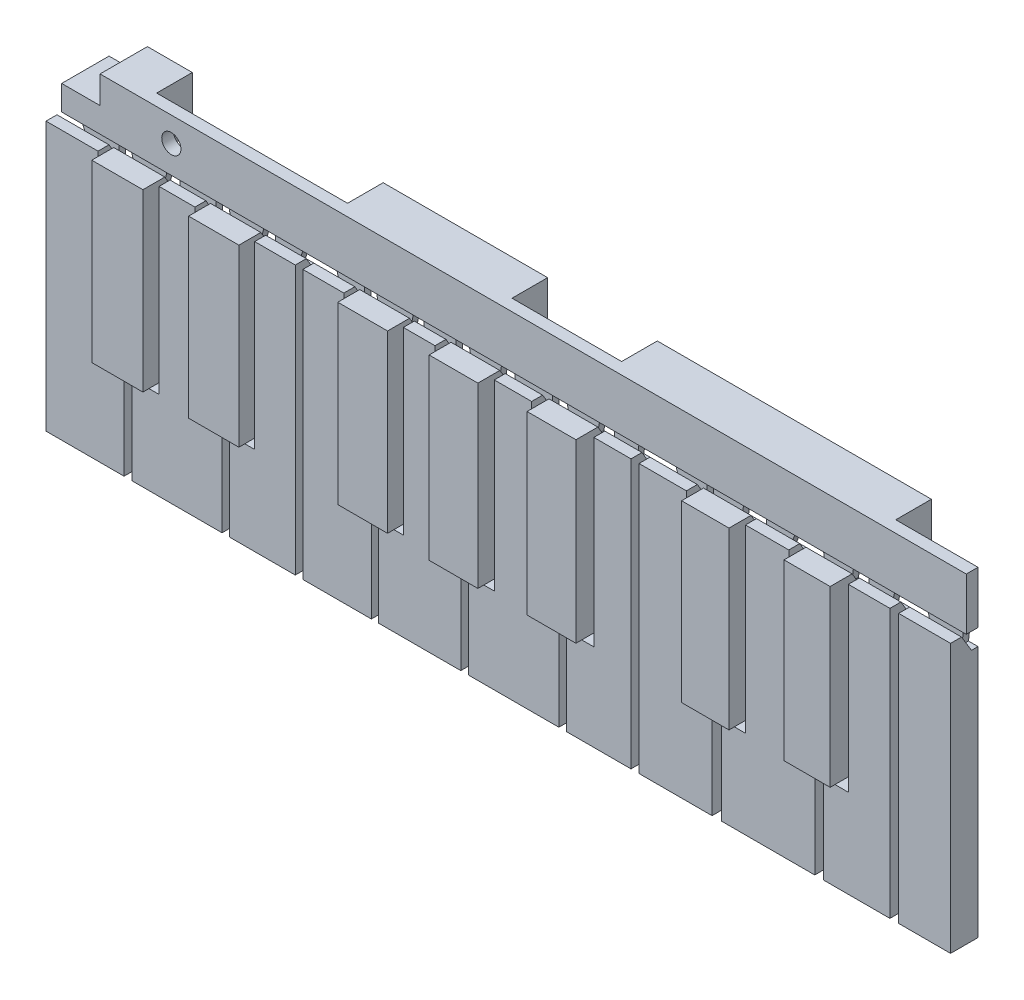
SolidWorks part; units mm, degrees
ref_plane "前视基准面" through (0, 0, 0) normal (0, 0, 1) x (1, 0, 0)
ref_plane "上视基准面" through (0, 0, 0) normal (0, 1, 0) x (1, 0, 0)
ref_plane "右视基准面" through (0, 0, 0) normal (1, 0, 0) x (0, 0, -1)
sketch "草图1" plane through (0, 0, 0) normal (0, 0, 1) x (1, 0, 0)
  line L1 (-72.6119, 33.3575) -> (92.3881, 33.3575)
  line L2 (-72.6119, 33.3575) -> (-72.6119, -26.6425)
  line L3 (-72.6119, -26.6425) -> (92.3881, -26.6425)
  line L4 (92.3881, 33.3575) -> (92.3881, -26.6425)
  dimension "D1" = 165
  dimension "D2" = 60
extrude "凸台-拉伸1" add sketch "草图1" along normal blind 5
sketch "草图2" plane through (0, 0, 5) normal (0, 0, 1) x (1, 0, 0)
  line L0 (-72.6119, 33.3575) -> (-72.6119, -26.6425) construction
  line L1 (92.3881, 33.3575) -> (-72.6119, 33.3575) construction
  circle A0 centre (-52.6119, 27.3575) radius 1.75
  dimension "D1" = 3.5
  dimension "D2" = 20
  dimension "D3" = 6
extrude "切除-拉伸1" cut sketch "草图2" against normal blind 30
sketch "草图3" plane through (0, 0, 5) normal (0, 0, 1) x (1, 0, 0)
  line L0 (-57.6119, 33.3575) -> (-57.6119, 22.3365)
  line L1 (92.3881, 33.3575) -> (-72.6119, 33.3575) construction
  line L2 (-72.6119, -26.6425) -> (92.3881, -26.6425) construction
  line L3 (-72.6119, 33.3575) -> (-72.6119, -26.6425) construction
  line L4 (-42.6119, 22.3365) -> (-42.6119, 33.3575)
  line L5 (-27.6119, 22.3365) -> (-27.6119, 33.3575)
  line L6 (-12.6119, 22.3365) -> (-12.6119, 33.3575)
  line L7 (2.3881, 22.3365) -> (2.3881, 33.3575)
  line L8 (17.3881, 22.3365) -> (17.3881, 33.3575)
  line L9 (32.3881, 22.3365) -> (32.3881, 33.3575)
  line L10 (47.3881, 22.3365) -> (47.3881, 33.3575)
  line L11 (62.3881, 22.3365) -> (62.3881, 33.3575)
  line L12 (77.3881, 22.3365) -> (77.3881, 33.3575)
  line L13 (92.3881, -26.6425) -> (92.3881, 33.3575)
  line L14 (-63.1231, 22.3365) -> (-63.1231, -10.5291)
  line L15 (-72.6119, 33.3575) -> (92.3881, 33.3575)
  line L16 (-72.6119, 33.3575) -> (-72.6119, 22.3365)
  line L17 (-72.6119, 22.3365) -> (92.3881, 22.3365)
  line L18 (92.3881, 33.3575) -> (92.3881, 22.3365)
  line L19 (-62.2658, 22.3365) -> (-52.9387, 22.3365)
  line L20 (-62.2658, 22.3365) -> (-62.2658, -9.6307)
  line L21 (-62.2658, -9.6307) -> (-52.9387, -9.6307)
  line L22 (-52.9387, 22.3365) -> (-52.9387, -9.6307)
  line L23 (-44.5975, 22.3365) -> (-35.4264, 22.3365)
  line L24 (-44.5975, 22.3365) -> (-44.5975, -9.5883)
  line L25 (-44.5975, -9.5883) -> (-35.4264, -9.5883)
  line L26 (-35.4264, 22.3365) -> (-35.4264, -9.5883)
  line L27 (-17.3914, 22.3365) -> (-8.3121, 22.3365)
  line L28 (-17.3914, 22.3365) -> (-17.3914, -9.6307)
  line L29 (-17.3914, -9.6307) -> (-8.3121, -9.6307)
  line L30 (-8.3121, 22.3365) -> (-8.3121, -9.6307)
  line L31 (-0.7328, 22.3365) -> (8.1631, 22.3365)
  line L32 (-0.7328, 22.3365) -> (-0.7328, -10.1031)
  line L33 (-0.7328, -10.1031) -> (8.1631, -10.1031)
  line L34 (8.1631, 22.3365) -> (8.1631, -10.1031)
  line L35 (17.1354, 22.3365) -> (26.0513, 22.3365)
  line L36 (17.1354, 22.3365) -> (17.1354, -9.8183)
  line L37 (17.1354, -9.8183) -> (26.0513, -9.8183)
  line L38 (26.0513, 22.3365) -> (26.0513, -9.8183)
  line L39 (64.0101, 22.3365) -> (72.4216, 22.3365)
  line L40 (64.0101, 22.3365) -> (64.0101, -9.3895)
  line L41 (64.0101, -9.3895) -> (72.4216, -9.3895)
  line L42 (72.4216, 22.3365) -> (72.4216, -9.3895)
  line L43 (53.9662, 22.3365) -> (45.3232, 22.3365)
  line L44 (53.9662, 22.3365) -> (53.9662, -9.5503)
  line L45 (53.9662, -9.5503) -> (45.3232, -9.5503)
  line L46 (45.3232, 22.3365) -> (45.3232, -9.5503)
  line L47 (-63.1231, -10.5291) -> (-58.3767, -10.5291)
  line L48 (-58.3767, -10.5291) -> (-58.3767, -26.6425)
  line L49 (-51.9859, 22.3365) -> (-51.9859, -10.5291)
  line L50 (-51.9859, -10.5291) -> (-56.9239, -10.5291)
  line L51 (-56.9239, -10.5291) -> (-56.9239, -26.6425)
  line L52 (-45.4469, 22.3365) -> (-45.4469, -10.5043)
  line L53 (-45.4469, -10.5043) -> (-40.4974, -10.5043)
  line L54 (-40.4974, -10.5043) -> (-40.4974, -26.6425)
  line L55 (-34.5468, 22.3365) -> (-34.5468, -10.5043)
  line L56 (-34.5468, -10.5043) -> (-39.1403, -10.5043)
  line L57 (-39.1403, -10.5043) -> (-39.1403, -26.6425)
  line L58 (-27.14, 22.3365) -> (-27.14, -26.6425)
  line L59 (-25.7583, 22.3365) -> (-25.7583, -26.6425)
  line L60 (-18.2877, 22.3365) -> (-18.2877, -10.4718)
  line L61 (-18.2877, -10.4718) -> (-13.2634, -10.4718)
  line L62 (-13.2634, -10.4718) -> (-13.2634, -26.6425)
  line L63 (-7.4304, 22.3365) -> (-7.4304, -10.4718)
  line L64 (-7.4304, -10.4718) -> (-11.9858, -10.4718)
  line L65 (-11.9858, -10.4718) -> (-11.9858, -26.6425)
  line L66 (-1.6558, 22.3365) -> (-1.6558, -11.0171)
  line L67 (-1.6558, -11.0171) -> (3.0505, -11.0171)
  line L68 (3.0505, -11.0171) -> (3.0505, -26.6425)
  line L69 (9.158, 22.3365) -> (9.158, -11.0171)
  line L70 (9.158, -11.0171) -> (4.4188, -11.0171)
  line L71 (4.4188, -11.0171) -> (4.4188, -26.6425)
  line L72 (15.9637, 22.3365) -> (15.9637, -10.7534)
  line L73 (15.9637, -10.7534) -> (20.9325, -10.7534)
  line L74 (20.9325, -10.7534) -> (20.9325, -26.6425)
  line L75 (27.321, 22.3365) -> (27.321, -10.7534)
  line L76 (27.321, -10.7534) -> (22.3104, -10.7534)
  line L77 (22.3104, -10.7534) -> (22.3104, -26.6425)
  line L78 (34.0942, 22.3365) -> (34.0942, -26.6425)
  line L79 (35.5607, 22.3365) -> (35.5607, -26.6425)
  line L80 (44.1986, 22.3365) -> (44.1986, -10.5733)
  line L81 (44.1986, -10.5733) -> (48.8752, -10.5733)
  line L82 (48.8752, -10.5733) -> (48.8752, -26.6425)
  line L83 (54.976, 22.3365) -> (54.976, -10.5733)
  line L84 (54.976, -10.5733) -> (50.5953, -10.5733)
  line L85 (50.5953, -10.5733) -> (50.5953, -26.6425)
  line L86 (62.8709, 22.3365) -> (62.8709, -10.5107)
  line L87 (62.8709, -10.5107) -> (67.6117, -10.5107)
  line L88 (67.6117, -10.5107) -> (67.6117, -26.6425)
  line L89 (73.7369, 22.3365) -> (73.7369, -10.5107)
  line L90 (73.7369, -10.5107) -> (69.2479, -10.5107)
  line L91 (69.2479, -10.5107) -> (69.2479, -26.6425)
  line L92 (81.3215, 22.3365) -> (81.3215, -26.6425)
  line L93 (82.9157, 22.3365) -> (82.9157, -26.6425)
  line M5 (-72.6119, -26.6425) -> (92.3881, -26.6425)
  dimension "D1" = 15
  dimension "D2" = 15
  dimension "D3" = 10
extrude "切除-拉伸2" cut sketch "草图3" against normal blind 30 contours L51 L50 L49 L17 L22 L21 L20 L14 L47 L48 M5 | L57 L56 L55 L17 L26 L25 L24 L52 L53 L54 M5 | L59 L17 L58 M5 | L65 L64 L63 L17 L30 L29 L28 L60 L61 L62 M5 | L71 L70 L69 L17 L34 L33 L32 L66 L67 L68 M5 | L77 L76 L75 L17 L38 L37 L36 L72 L73 L74 M5 | L79 L17 L78 M5 | L85 L84 L83 L17 L44 L45 L46 L80 L81 L82 M5 | L91 L90 L89 L17 L42 L41 L40 L86 L87 L88 M5 | L93 L17 L92 M5
sketch "草图4" plane through (0, 0, 5) normal (0, 0, 1) x (1, 0, 0)
  line L1 (-62.2658, 22.3365) -> (-52.9387, 22.3365)
  line L2 (-62.2658, 22.3365) -> (-62.2658, -9.6307)
  line L3 (-62.2658, -9.6307) -> (-52.9387, -9.6307)
  line L4 (-52.9387, 22.3365) -> (-52.9387, -9.6307)
  line L5 (-44.5975, 22.3365) -> (-35.4264, 22.3365)
  line L6 (-44.5975, 22.3365) -> (-44.5975, -9.5883)
  line L7 (-44.5975, -9.5883) -> (-35.4264, -9.5883)
  line L8 (-35.4264, 22.3365) -> (-35.4264, -9.5883)
  line L9 (-17.3914, 22.3365) -> (-8.3121, 22.3365)
  line L10 (-17.3914, 22.3365) -> (-17.3914, -9.6307)
  line L11 (-17.3914, -9.6307) -> (-8.3121, -9.6307)
  line L12 (-8.3121, 22.3365) -> (-8.3121, -9.6307)
  line L13 (-0.7328, 22.3365) -> (8.1631, 22.3365)
  line L14 (-0.7328, 22.3365) -> (-0.7328, -10.1031)
  line L15 (-0.7328, -10.1031) -> (8.1631, -10.1031)
  line L16 (8.1631, 22.3365) -> (8.1631, -10.1031)
  line L17 (17.1354, 22.3365) -> (26.0513, 22.3365)
  line L18 (17.1354, 22.3365) -> (17.1354, -9.8183)
  line L19 (17.1354, -9.8183) -> (26.0513, -9.8183)
  line L20 (26.0513, 22.3365) -> (26.0513, -9.8183)
  line L21 (45.3232, 22.3365) -> (53.9662, 22.3365)
  line L22 (45.3232, 22.3365) -> (45.3232, -9.5503)
  line L23 (45.3232, -9.5503) -> (53.9662, -9.5503)
  line L24 (53.9662, 22.3365) -> (53.9662, -9.5503)
  line L25 (64.0101, 22.3365) -> (72.4216, 22.3365)
  line L26 (64.0101, 22.3365) -> (64.0101, -9.3895)
  line L27 (64.0101, -9.3895) -> (72.4216, -9.3895)
  line L28 (72.4216, 22.3365) -> (72.4216, -9.3895)
extrude "凸台-拉伸2" add sketch "草图4" along normal blind 2
sketch "草图5" plane through (-72.6119, 0, 0) normal (-1, 0, 0) x (0, 0, 1)
  line L0 (5, 22.3365) -> (3, 22.3365)
  line L1 (3, 22.3365) -> (1.2, 19.3365)
  line L2 (1.2, 19.3365) -> (0, 19.3365)
  line L3 (0, 33.3575) -> (0, -26.6425) construction
  line L4 (1.2, 19.3365) -> (1.2, 22.3365)
  line L5 (2.1394, 22.3365) -> (2.1394, 33.3575)
  line L6 (5, 33.3575) -> (0, 33.3575) construction
  line L7 (2.1394, 22.3365) -> (1.2, 22.3365)
  line M3 (5, -26.6425) -> (5, 33.3575)
  line M4 (5, 33.3575) -> (0, 33.3575)
  dimension "D1" = 2
  dimension "D2" = 1.2
  dimension "D3" = 3
extrude "切除-拉伸3" cut sketch "草图5" against normal blind 180 contours L5 L7 L4 L1 L0 M3 M4
sketch "草图6" plane through (0, 0, 0) normal (0, 0, -1) x (-1, 0, 0)
  line L0 (-82.9157, 22.3365) -> (-92.3881, 22.3365)
  line L1 (-92.3881, 22.3365) -> (72.6119, 22.3365)
  line L2 (-92.3881, 19.3365) -> (72.6119, 19.3365)
  line L3 (-92.3881, -26.6425) -> (-92.3881, 33.3575) construction
  line L4 (72.6119, 33.3575) -> (72.6119, -26.6425) construction
  line L5 (-84.4644, 22.3365) -> (-84.8066, 19.3365)
  line L6 (-91.0057, 22.3365) -> (-90.6456, 19.3365)
  line L7 (-78.5528, 22.3365) -> (-77.9066, 19.3365)
  line L8 (-70.9869, 22.3365) -> (-70.5747, 19.3365)
  line L9 (-65.3343, 22.3365) -> (-65.6606, 19.3365)
  line L10 (-50.9334, 22.3365) -> (-50.5469, 19.3365)
  line L12 (-38.233, 22.3365) -> (-39.1842, 19.3365)
  line L13 (-31.8532, 22.3365) -> (-31.4297, 19.3365)
  line L14 (-24.7337, 22.3365) -> (-24.1308, 19.3365)
  line L15 (-18.5612, 22.3365) -> (-19.0107, 19.3365)
  line L16 (-6.7996, 22.3365) -> (-6.3302, 19.3365)
  line L17 (-0.6829, 22.3365) -> (-1.2137, 19.3365)
  line L18 (9.2347, 22.3365) -> (9.8547, 19.3365)
  line L19 (16.2073, 22.3365) -> (15.722, 19.3365)
  line L20 (23.6214, 22.3365) -> (22.7103, 19.3365)
  line L21 (29.2964, 22.3365) -> (30.2687, 19.3365)
  line L22 (36.4457, 22.3365) -> (37.2453, 19.3365)
  line L23 (43.1402, 22.3365) -> (42.611, 19.3365)
  line L24 (54.1265, 22.3365) -> (54.8939, 19.3365)
  line L25 (61.0385, 22.3365) -> (60.2273, 19.3365)
  line L26 (70.1185, 22.3365) -> (68.8341, 19.3365)
  line L27 (-92.3881, 22.3365) -> (-92.3881, 19.3365)
  line L28 (-92.3881, 22.3365) -> (-92.3881, 19.3365)
  line L29 (72.6119, 22.3365) -> (72.6119, 19.3365)
  line L30 (-92.3881, 22.3365) -> (-92.3881, 19.3365)
  line L31 (-72.4216, 22.3365) -> (-72.4216, 19.3365)
  line L32 (-64.0101, 22.3365) -> (-64.0101, 19.3365)
  line L33 (-53.9662, 22.3365) -> (-53.9662, 19.3365)
  line L34 (-45.3232, 22.3365) -> (-45.3232, 19.3365)
  line L35 (-26.0513, 22.3365) -> (-26.0513, 19.3365)
  line L36 (-17.1354, 22.3365) -> (-17.1354, 19.3365)
  line L37 (-8.1631, 22.3365) -> (-8.1631, 19.3365)
  line L38 (0.7328, 22.3365) -> (0.7328, 19.3365)
  line L39 (0.7328, 22.3365) -> (0.7328, -10.1031) construction
  line L40 (8.3121, 22.3365) -> (8.3121, 19.3365)
  line L41 (17.3914, 22.3365) -> (17.3914, 19.3365)
  line L42 (35.4264, 22.3365) -> (35.4264, 19.3365)
  line L43 (44.5975, 22.3365) -> (44.5975, 19.3365)
  line L44 (52.9387, 22.3365) -> (52.9387, 19.3365)
  line L45 (62.2658, 22.3365) -> (62.2658, 19.3365)
  line L46 (-60.581, 22.3365) -> (-59.2938, 19.3365)
  line L47 (-62.8709, 22.3365) -> (-62.8709, 19.3365)
  line L48 (-62.8709, 22.3365) -> (-62.8709, -10.5107) construction
  dimension "D1" = 3
extrude "切除-拉伸4" cut sketch "草图6" against normal blind 1.2 contours L0 L27 L2 L6 | L7 L1 L0 L5 L2 | L1 L31 L2 L8 | L32 L1 L9 L2 | L13 L1 L12 L2 | L1 L35 L2 L14 | L36 L1 L15 L2 | L1 L37 L2 L16 | L38 L1 L17 L2 | L1 L40 L2 L18 | L41 L1 L19 L2 | L21 L1 L20 L2 | L1 L42 L2 L22 | L43 L1 L23 L2 | L1 L44 L2 L24 | L45 L1 L25 L2 | L29 L1 L26 L2 | L1 L47 L2 L46 | L1 L33 L2 L10
sketch "草图7" plane through (0, 0, 0) normal (0, 0, -1) x (-1, 0, 0)
  line L0 (22.6119, 33.3575) -> (22.6119, 22.3365)
  line L1 (-92.3881, 33.3575) -> (72.6119, 33.3575)
  line L2 (-92.3881, 33.3575) -> (-92.3881, 22.3365)
  line L3 (-92.3881, 22.3365) -> (72.6119, 22.3365)
  line L4 (72.6119, 33.3575) -> (72.6119, 22.3365)
  line L5 (-7.3881, 33.3575) -> (-7.3881, 22.3365)
  line L6 (-27.3881, 33.3575) -> (-27.3881, 22.3365)
  line L7 (-77.3881, 33.3575) -> (-77.3881, 22.3365)
  line L8 (57.4281, 33.3575) -> (57.4281, 22.3365)
  circle A0 centre (52.6119, 27.3575) radius 1.75 construction
  point P16 (-77.3881, 27.847)
  dimension "D1" = 30
  dimension "D3" = 80
  dimension "D4" = 130
  dimension "D2" = 30
extrude "凸台-拉伸5" add sketch "草图7" along normal blind 6.5 contours L1 L7 L3 L6 | L1 L5 L3 L0 | L1 L8 L3 L4
sketch "草图9" plane through (0, 0, 2.1394) normal (0, 0, 1) x (1, 0, 0)
  line L1 (-72.6119, 33.3575) -> (-65.6119, 33.3575)
  line L2 (-72.6119, 33.3575) -> (-72.6119, 26.8575)
  line L3 (-72.6119, 26.8575) -> (-65.6119, 26.8575)
  line L4 (-65.6119, 33.3575) -> (-65.6119, 26.8575)
  dimension "D1" = 6.5
  dimension "D2" = 7
extrude "切除-拉伸6" cut sketch "草图9" against normal blind 24
sketch "草图10" plane through (0, 0, 2.1394) normal (0, 0, 1) x (1, 0, 0)
  line L0 (92.3881, 22.3365) -> (92.3881, 33.3575) construction
  line L1 (-65.6119, 33.3575) -> (92.3881, 33.3575)
  line L2 (-65.6119, 33.3575) -> (-65.6119, 31.8575)
  line L3 (-65.6119, 31.8575) -> (92.3881, 31.8575)
  line L4 (92.3881, 33.3575) -> (92.3881, 31.8575)
  dimension "D1" = 1.5
extrude "切除-拉伸7" cut sketch "草图10" against normal blind 10 contours L2 L1 L4 L3
